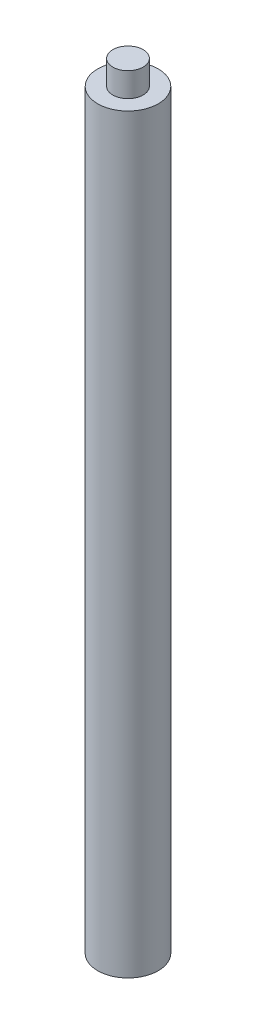
SolidWorks part; units mm, degrees
ref_plane "Front Plane" through (0, 0, 0) normal (0, 0, 1) x (1, 0, 0)
ref_plane "Top Plane" through (0, 0, 0) normal (0, 1, 0) x (1, 0, 0)
ref_plane "Right Plane" through (0, 0, 0) normal (1, 0, 0) x (0, 0, -1)
sketch "Sketch1" plane through (0, 0, 0) normal (0, 1, 0) x (1, 0, 0)
  circle A0 centre (0, 0) radius 10
  dimension "D1" = 20
extrude "Boss-Extrude1" add sketch "Sketch1" along normal mid plane 248
sketch "Sketch2" plane through (0, 124, 0) normal (0, 1, 0) x (1, 0, 0)
  circle A0 centre (0, 0) radius 5
  dimension "D1" = 10
extrude "Boss-Extrude2" add sketch "Sketch2" along normal blind 8
